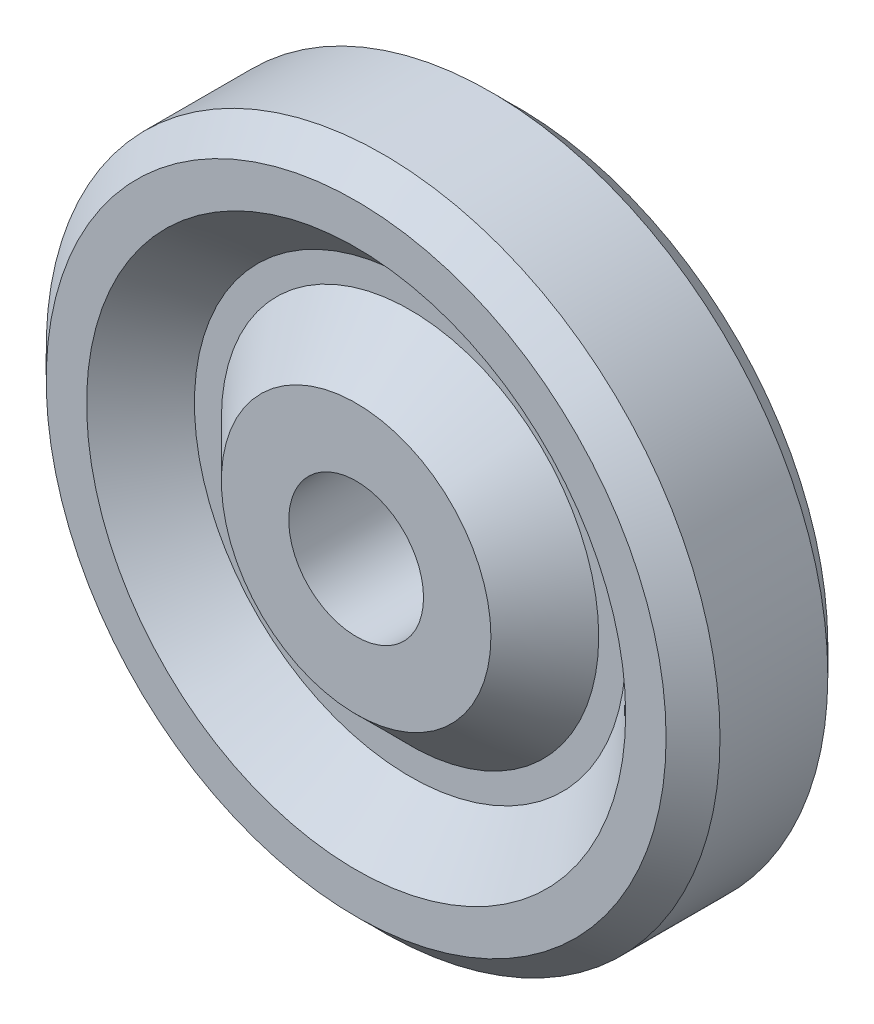
SolidWorks part; units mm, degrees
ref_plane "Front Plane" through (0, 0, 0) normal (0, 0, 1) x (1, 0, 0)
ref_plane "Top Plane" through (0, 0, 0) normal (0, 1, 0) x (1, 0, 0)
ref_plane "Right Plane" through (0, 0, 0) normal (1, 0, 0) x (0, 0, -1)
sketch "Sketch2" plane through (0, 0, 0) normal (0, 0, 1) x (1, 0, 0)
  circle A0 centre (0, 0) radius 12.5
  dimension "D1" = 25
extrude "Boss-Extrude1" add sketch "Sketch2" along normal mid plane 6
sketch "Sketch3" plane through (0, 0, 3) normal (0, 0, 1) x (1, 0, 0)
  circle A0 centre (0, 0) radius 2.5
  dimension "D1" = 5
extrude "Cut-Extrude1" cut sketch "Sketch3" against normal blind 6
sketch "Sketch4" plane through (0, 0, 3) normal (0, 0, 1) x (1, 0, 0)
  circle A2 centre (0, 0) radius 10
  circle A3 centre (0, 0) radius 10
  circle A5 centre (0, 0) radius 5
  circle A6 centre (0, 0) radius 5
  dimension "D1" = 2.5
  dimension "D2" = 2.5
extrude "Cut-Extrude2" cut sketch "Sketch4" against normal blind 2 draft 45
mirror "Mirror1" about plane through (0, 0, 0) normal (0, 0, 1) of "Cut-Extrude2"
chamfer "Chamfer1" distance 1 angle 45 2 edges at (12.5, 0, 3) (12.5, 0, -3)
